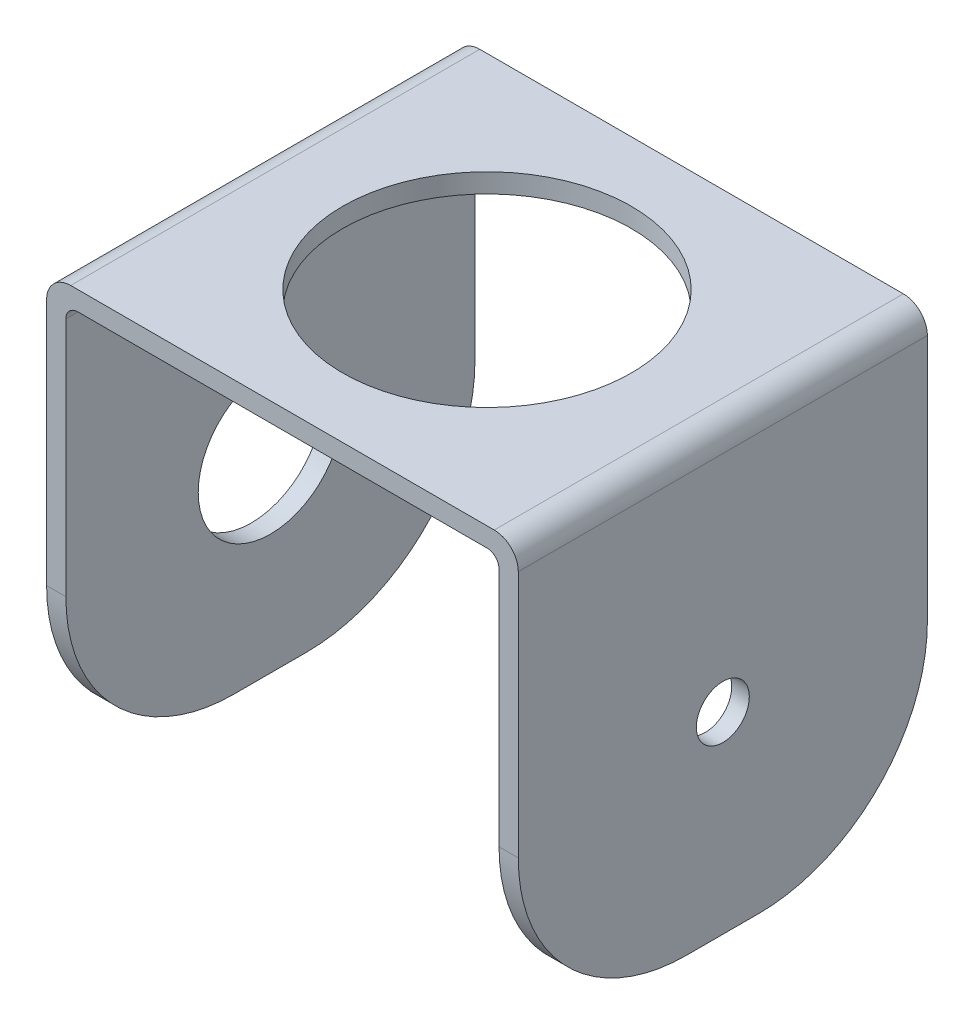
SolidWorks part; units mm, degrees
material "6061 合金"
ref_plane "前视基准面" through (0, 0, 0) normal (0, 0, 1) x (1, 0, 0)
ref_plane "上视基准面" through (0, 0, 0) normal (0, 1, 0) x (1, 0, 0)
ref_plane "右视基准面" through (0, 0, 0) normal (1, 0, 0) x (0, 0, -1)
other "Configuration Table"
sketch "草图1" plane through (0, 0, 0) normal (0, 0, 1) x (1, 0, 0)
  line L0 (-180, 0) -> (0, 0)
  line L1 (0, 0) -> (0, -175)
  line L3 (8, -175) -> (8, 8)
  line L4 (8, 8) -> (-180, 8)
  line L6 (0, -175) -> (8, -175)
  line L12 (-180, 8) -> (-188, 8)
  line L13 (-180, 0) -> (-180, -175)
  line L14 (-180, -175) -> (-188, -175)
  line L15 (-188, 8) -> (-188, -175)
  dimension "D1" = 8
  dimension "D2" = 8
  dimension "D4" = 180
  dimension "D5" = 183
  dimension "D6" = 8
  dimension "D8" = 8
extrude "凸台-拉伸1" add sketch "草图1" along normal blind 170
sketch "草图2" plane through (0, 8, 0) normal (0, 1, 0) x (1, 0, 0)
  line L0 (-216.3195, -85) -> (51.5119, -85) construction
  line L1 (8, -170) -> (-188, -170) construction
  line L2 (8, 0) -> (-188, 0) construction
  line L7 (-90, -75.3242) -> (-90, -92.2023) construction
  line L8 (8, -170) -> (8, 0) construction
  line L9 (-188, -170) -> (-188, 0) construction
  circle A2 centre (-90, -85) radius 60
  dimension "D3" = 120
extrude "切除-拉伸1" cut sketch "草图2" against normal blind 180 contours A2 L0 | L0 A2
sketch "草图3" plane through (8, 0, 0) normal (1, 0, 0) x (0, 0, -1)
  line L0 (-85, 25.6845) -> (-85, -173.3318) construction
  line L1 (0, -175) -> (0, 8) construction
  line L2 (-170, -175) -> (-170, 8) construction
  line L3 (-170, -175) -> (0, -175) construction
  line L4 (0, 0) -> (-209.686, 0) construction
  circle A0 centre (-85, -95) radius 11
  dimension "D1" = 22
  dimension "D2" = 80
extrude "切除-拉伸2" cut sketch "草图3" against normal through all both and the other way through all contours A0
fillet "圆角1" radius 70 4 edges at (-184, -175, 170) (-184, -175, 0) (4, -175, 0) (4, -175, 170)
fillet "圆角2" radius 5 2 edges at (-180, 0, 85) (0, 0, 85)
fillet "圆角3" radius 10 2 edges at (8, 8, 85) (-188, 8, 85)
sketch "草图6" plane through (-188, 0, 0) normal (-1, 0, 0) x (0, 0, 1)
  circle A0 centre (85, -95) radius 30
  dimension "D1" = 60
extrude "切除-拉伸6" cut sketch "草图6" against normal blind 39
sketch "草图7" plane through (0, 0, 0) normal (-1, 0, 0) x (0, 0, 1)
  circle A0 centre (85, -95) radius 13
  dimension "D1" = 26
extrude "切除-拉伸7" cut sketch "草图7" against normal blind 0.7
